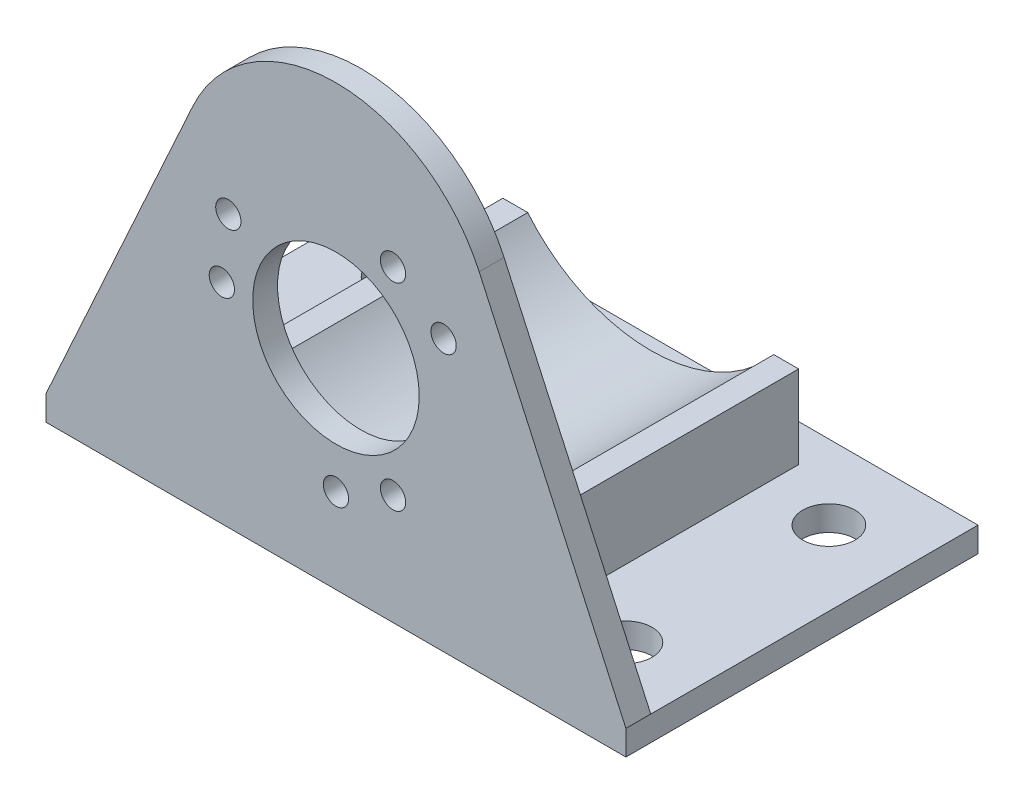
SolidWorks part; units mm, degrees
material "Plain Carbon Steel"
ref_plane "Front Plane" through (0, 0, 0) normal (0, 0, 1) x (1, 0, 0)
ref_plane "Top Plane" through (0, 0, 0) normal (0, 1, 0) x (1, 0, 0)
ref_plane "Right Plane" through (0, 0, 0) normal (1, 0, 0) x (0, 0, -1)
sketch "Sketch3" plane through (0, 0, 0) normal (0, 1, 0) x (1, 0, 0)
  line L1 (-35, 21.25) -> (35, 21.25)
  line L2 (-35, 21.25) -> (-35, -21.25)
  line L3 (-35, -21.25) -> (35, -21.25)
  line L4 (35, 21.25) -> (35, -21.25)
  line L5 (-35, 21.25) -> (35, -21.25) construction
  line L6 (-35, -21.25) -> (35, 21.25) construction
  point P0 (0, 0)
  dimension "D1" = 42.5
  dimension "D2" = 70
extrude "Boss-Extrude1" add sketch "Sketch3" along normal blind 3
sketch "Sketch4" plane through (0, 0, 21.25) normal (0, 0, 1) x (1, 0, 0)
  line L0 (-35, 3) -> (-17.2905, 41.8764)
  line L1 (17.2905, 41.8764) -> (35, 3)
  line L2 (0, 53) -> (0, 3) construction
  line L3 (-35, 3) -> (35, 3) construction
  line L4 (-24.8644, 25.25) -> (24.8644, 25.25) construction
  line L5 (-12.9904, 32.75) -> (0, 25.25) construction
  line L6 (-35, 3) -> (35, 3)
  arc A0 (17.2905, 41.8764) -> (-17.2905, 41.8764) centre (0, 34) ccw
  circle A1 centre (0, 25.25) radius 19.25 construction
  circle A2 centre (0, 25.25) radius 10.05
  circle A3 centre (0, 25.25) radius 14 construction
  circle A4 centre (0, 25.25) radius 15 construction
  circle A6 centre (-13.7748, 25.25) radius 1.525
  circle A7 centre (-12.9904, 32.75) radius 1.525
  circle A8 centre (12.9904, 32.75) radius 1.525
  circle A9 centre (6.8874, 37.1793) radius 1.525
  circle A10 centre (0, 10.25) radius 1.525
  circle A11 centre (6.8874, 13.3207) radius 1.525
  point P33 (0, 25.25)
  dimension "D1" = 19
  dimension "D2" = 38.5
  dimension "D3" = 22.25
  dimension "D4" = 20.1
  dimension "D5" = 28
  dimension "D6" = 30
  dimension "D8" = 3.05
  dimension "D7" = 30
  dimension "D10" = 50
  dimension "D9" = 3
extrude "Boss-Extrude2" add sketch "Sketch4" against normal blind 3
sketch "Sketch5" plane through (0, 0, 18.25) normal (0, 0, -1) x (-1, 0, 0)
  line L0 (-17.8492, 3) -> (-17.8492, 13)
  line L1 (-35, 3) -> (35, 3) construction
  line L2 (-17.8492, 13) -> (17.8492, 13)
  line L3 (17.8492, 13) -> (17.8492, 3)
  line L4 (17.8492, 3) -> (-17.8492, 3)
  line L5 (0, 25.25) -> (0, 3) construction
  line L6 (35, 3) -> (-35, 3) construction
  line L7 (14.8492, 13) -> (14.8492, 3) construction
  circle A0 centre (0, 25.25) radius 19.25
  point P12 (0, 3)
  line M14 (-35, 3) -> (35, 3)
  dimension "D2" = 38.5
  dimension "D1" = 3
  dimension "D3" = 10
extrude "Boss-Extrude3" add sketch "Sketch5" along normal blind 35 contours A0 L2 L0 L3 M14
sketch "Sketch6" plane through (0, 3, 0) normal (0, 1, 0) x (1, 0, 0)
  line L0 (0, 21.25) -> (0, -18.25) construction
  line L1 (35, 21.25) -> (-35, 21.25) construction
  line L2 (17.2905, -18.25) -> (-17.2905, -18.25) construction
  line L3 (-35, 0) -> (35, 0) construction
  line L4 (-35, 21.25) -> (-35, -18.25) construction
  line L5 (35, -18.25) -> (35, 21.25) construction
  circle A0 centre (-26, 12.25) radius 3.15
  circle A1 centre (26, 12.25) radius 3.15
  circle A2 centre (26, -12.25) radius 3.15
  circle A3 centre (-26, -12.25) radius 3.15
  dimension "D3" = 6.3
  dimension "D1" = 9
  dimension "D2" = 9
extrude "Cut-Extrude1" cut sketch "Sketch6" against normal blind 5
